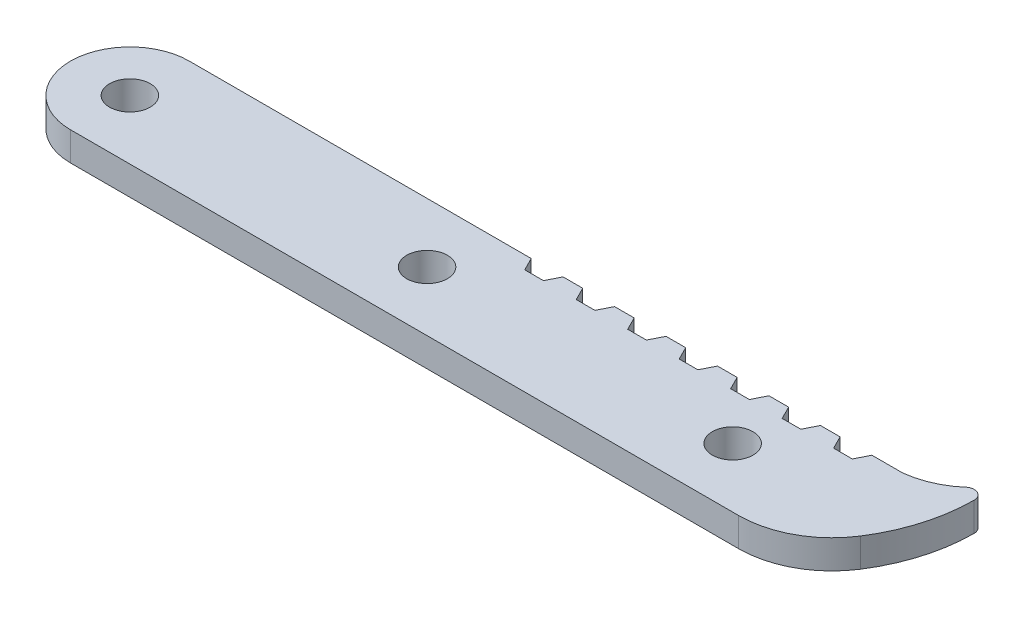
SolidWorks part; units mm, degrees
material "PET"
ref_plane "Front" through (0, 0, 0) normal (0, 0, 1) x (1, 0, 0)
ref_plane "Top" through (0, 0, 0) normal (0, 1, 0) x (1, 0, 0)
ref_plane "Right" through (0, 0, 0) normal (1, 0, 0) x (0, 0, -1)
sketch "Sketch1" plane through (0, 0, 0) normal (0, 1, 0) x (1, 0, 0)
  line L1 (-62.8447, 8.7002) -> (13.3553, 8.7002)
  line L3 (-62.8447, -3.9998) -> (13.3553, -3.9998)
  line L5 (-62.8447, 8.7002) -> (13.3553, -3.9998) construction
  line L6 (-62.8447, -3.9998) -> (13.3553, 8.7002) construction
  arc A0 (-62.8447, 8.7002) -> (-62.8447, -3.9998) centre (-62.8447, 2.3502) ccw
  arc A2 (13.3553, 8.7002) -> (13.3553, -3.9998) centre (13.3553, 2.3502) cw
  point P4 (-24.7447, 2.3502)
  dimension "D1" = 76.2
  dimension "D2" = 12.7
extrude "Boss-Extrude1" add sketch "Sketch1" along normal blind 3.075
sketch "Sketch2" plane through (0, 3.075, 0) normal (0, 1, 0) x (1, 0, 0)
  circle A0 centre (-62.8447, 2.3502) radius 2.175
  circle A1 centre (-31.0947, 2.3502) radius 2.175
  circle A2 centre (1.5553, 2.3502) radius 2.175
  arc A3 (13.3553, -3.9998) -> (13.3553, 8.7002) centre (13.3553, 2.3502) ccw construction
  dimension "D1" = 31.75
  dimension "D2" = 4.35
  dimension "D3" = 4.35
  dimension "D4" = 4.35
  dimension "D5" = 11.8
extrude "Cut-Extrude2" cut sketch "Sketch2" against normal blind 6.35
sketch "Sketch3" plane through (0, 3.075, 0) normal (0, 1, 0) x (1, 0, 0)
  line L2 (13.3553, 8.7002) -> (13.3553, 2.3502)
  line L7 (19.7053, 2.3502) -> (19.7053, 9.9994)
  line L8 (19.7053, 2.3502) -> (13.3553, 2.3502)
  arc A0 (13.3553, -3.9998) -> (13.3553, 8.7002) centre (13.3553, 2.3502) ccw construction
  arc A2 (19.7053, 9.9994) -> (18.1741, 10.8466) centre (18.7053, 9.9994) ccw
  arc A3 (18.1741, 10.8466) -> (13.3553, 8.7002) centre (12.37, 17.3945) cw
  point P4 (25.0274, 5.3951)
  dimension "D1" = 1
  dimension "D2" = 7.6492
  dimension "D3" = 6.35
  dimension "D5" = 1.75
  dimension "D6" = 8.75
  dimension "D4" = 6.35
extrude "Boss-Extrude2" add sketch "Sketch3" against normal up to vertex (3.075 mm away)
sketch "Sketch4" plane through (0, 3.075, 0) normal (0, 1, 0) x (1, 0, 0)
  line L1 (19.7053, 9.9994) -> (19.7053, -6.0006)
  line L2 (19.7053, -6.0006) -> (9.2053, -6.0006)
  arc A3 (19.7053, 9.9994) -> (9.2053, -6.0006) centre (2.2054, 10.0384) cw
  arc A4 (19.7053, 9.9994) -> (18.1741, 10.8466) centre (18.7053, 9.9994) ccw construction
  point P2 (0, 0)
  point P5 (0, 0)
  dimension "D1" = 16
  dimension "D3" = 17.5
  dimension "D2" = 10.5
extrude "Cut-Extrude3" cut sketch "Sketch4" against normal blind 10
fillet "Fillet1" radius 10 1 edges at (12.6542, 1.5375, 3.9998)
sketch "Sketch5" plane through (0, 3.075, 0) normal (0, 1, 0) x (1, 0, 0)
  line L0 (-4.3147, 8.7002) -> (-0.9147, 8.7002)
  line L1 (13.3553, 8.7002) -> (-62.8447, 8.7002) construction
  line L3 (-9.8147, 8.7002) -> (-9.1147, 7.306)
  line L4 (-9.1147, 7.306) -> (-7.1147, 7.306)
  line L5 (-7.1147, 7.306) -> (-6.4147, 8.7002)
  line L14 (-4.3147, 8.7002) -> (-3.6147, 7.306)
  line L18 (-9.8147, 8.7002) -> (-6.4147, 8.7002)
  line L19 (-3.6147, 7.306) -> (-1.6147, 7.306)
  line L20 (-1.6147, 7.306) -> (-0.9147, 8.7002)
  line L21 (1.1853, 8.7002) -> (4.5853, 8.7002)
  line L22 (1.1853, 8.7002) -> (1.8853, 7.306)
  line L23 (1.8853, 7.306) -> (3.8853, 7.306)
  line L24 (3.8853, 7.306) -> (4.5853, 8.7002)
  line L25 (6.6853, 8.7002) -> (10.0853, 8.7002)
  line L26 (6.6853, 8.7002) -> (7.3853, 7.306)
  line L27 (7.3853, 7.306) -> (9.3853, 7.306)
  line L28 (9.3853, 7.306) -> (10.0853, 8.7002)
  line L29 (-15.3147, 8.7002) -> (-11.9147, 8.7002)
  line L30 (-15.3147, 8.7002) -> (-14.6147, 7.306)
  line L31 (-14.6147, 7.306) -> (-12.6147, 7.306)
  line L32 (-12.6147, 7.306) -> (-11.9147, 8.7002)
  line L33 (-20.8147, 8.7002) -> (-17.4147, 8.7002)
  line L34 (-20.8147, 8.7002) -> (-20.1147, 7.306)
  line L35 (-20.1147, 7.306) -> (-18.1147, 7.306)
  line L36 (-18.1147, 7.306) -> (-17.4147, 8.7002)
  line L37 (-26.3147, 8.7002) -> (-22.9147, 8.7002)
  line L38 (-26.3147, 8.7002) -> (-25.6147, 7.306)
  line L39 (-25.6147, 7.306) -> (-23.6147, 7.306)
  line L40 (-23.6147, 7.306) -> (-22.9147, 8.7002)
  dimension "D1" = 4
  dimension "D2" = 4
  dimension "D3" = 2
  dimension "D4" = 1.56
  dimension "D5" = 1.56
extrude "Cut-Extrude4" cut sketch "Sketch5" against normal blind 10
